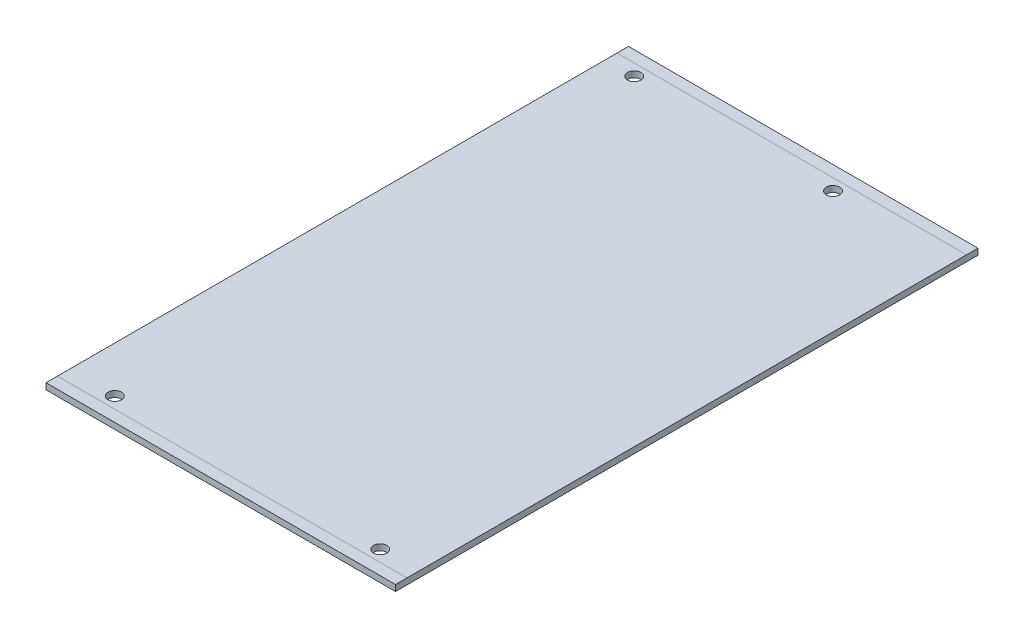
SolidWorks part; units mm, degrees
ref_plane "Front Plane" through (0, 0, 0) normal (0, 0, 1) x (1, 0, 0)
ref_plane "Top Plane" through (0, 0, 0) normal (0, 1, 0) x (1, 0, 0)
ref_plane "Right Plane" through (0, 0, 0) normal (1, 0, 0) x (0, 0, -1)
sketch "Sketch1" plane through (0, 0, 0) normal (0, 1, 0) x (1, 0, 0)
  line L1 (-45.72, -76.2) -> (45.72, -76.2)
  line L2 (-45.72, -76.2) -> (-45.72, 76.2)
  line L3 (-45.72, 76.2) -> (45.72, 76.2)
  line L4 (45.72, -76.2) -> (45.72, 76.2)
  line L5 (-45.72, -76.2) -> (45.72, 76.2) construction
  line L6 (-45.72, 76.2) -> (45.72, -76.2) construction
  point P0 (0, 0)
  dimension "D1" = 91.44
  dimension "D2" = 152.4
extrude "Boss-Extrude1" add sketch "Sketch1" along normal blind 1.6
sketch "Sketch2" plane through (0, 1.6, 0) normal (0, 1, 0) x (1, 0, 0)
  line L0 (-45.72, 76.2) -> (-45.72, -76.2) construction
  line L1 (-45.72, -76.2) -> (45.72, -76.2) construction
  line L2 (45.72, 76.2) -> (-45.72, 76.2) construction
  line L3 (45.72, 76.2) -> (-45.72, 76.2) construction
  line L5 (45.72, -76.2) -> (45.72, 76.2) construction
  circle A0 centre (-38.22, 70.2) radius 1.75
  circle A1 centre (-33.72, -70.2) radius 1.75
  circle A2 centre (35.72, -70.2) radius 1.75
  circle A3 centre (13.78, 70.2) radius 1.75
  dimension "D4" = 12
  dimension "D5" = 3.5
  dimension "D6" = 3.5
  dimension "D8" = 6
  dimension "D9" = 10
  dimension "D10" = 7.5
  dimension "D2" = 6
  dimension "D3" = 3.5
  dimension "D11" = 3.5
  dimension "D12" = 6
  dimension "D13" = 52
  dimension "D7" = 6
extrude "Cut-Extrude1" cut sketch "Sketch2" against normal up to next
sketch "Sketch3" plane through (0, 1.6, 0) normal (0, 1, 0) x (1, 0, 0)
  line L0 (45.72, -76.2) -> (45.72, 76.2) construction
  line L1 (-45.72, 76.2) -> (45.72, 76.2)
  line L2 (-45.72, 76.2) -> (-45.72, 73.2)
  line L3 (-45.72, 73.2) -> (45.72, 73.2)
  line L4 (45.72, 76.2) -> (45.72, 73.2)
  line L6 (-45.72, -76.2) -> (45.72, -76.2)
  line L7 (-45.72, -76.2) -> (-45.72, -73.2)
  line L8 (-45.72, -73.2) -> (45.72, -73.2)
  line L9 (45.72, -76.2) -> (45.72, -73.2)
  dimension "D1" = 3
  dimension "D2" = 3
extrude "Cut-Extrude2" cut sketch "Sketch3" against normal blind 0.0001
